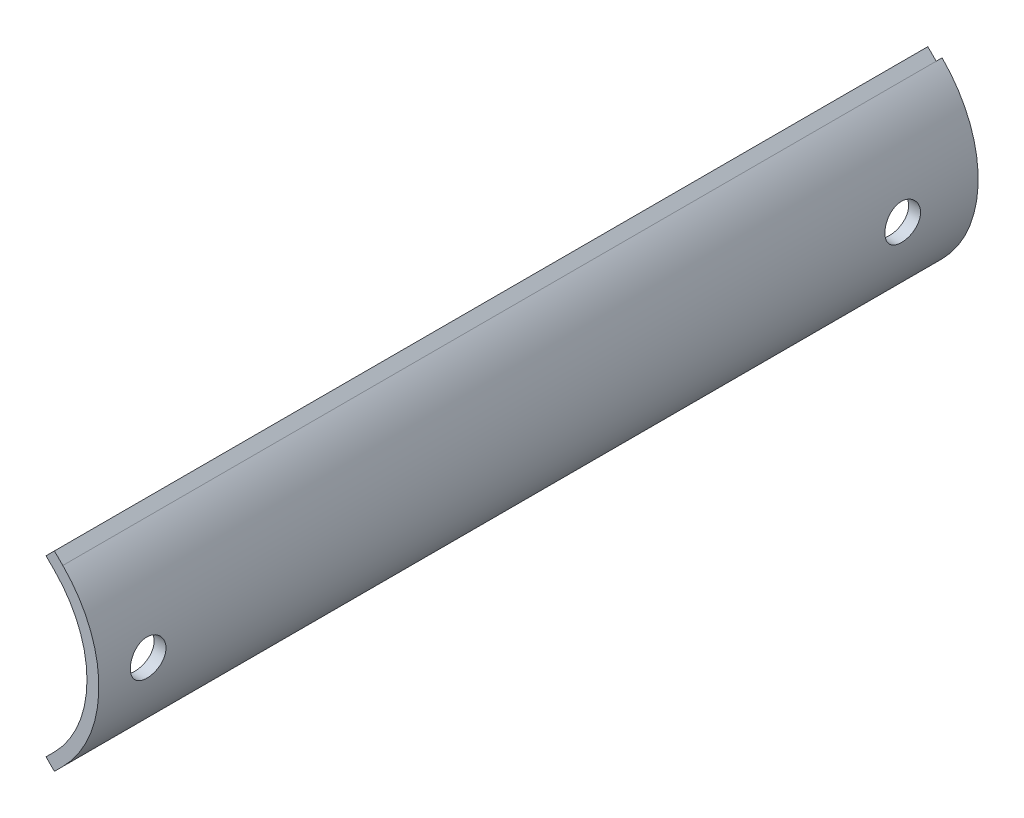
SolidWorks part; units mm, degrees
ref_plane "Front" through (0, 0, 0) normal (0, 0, 1) x (1, 0, 0)
ref_plane "Top" through (0, 0, 0) normal (0, 1, 0) x (1, 0, 0)
ref_plane "Right" through (0, 0, 0) normal (1, 0, 0) x (0, 0, -1)
sketch "Sketch1" plane through (0, 0, 0) normal (0, 0, 1) x (1, 0, 0)
  line L0 (6.6185, 6.6185) -> (7.3256, 7.3256)
  line L1 (6.6185, -6.6185) -> (7.3256, -7.3256)
  arc A0 (6.6185, 6.6185) -> (6.6185, -6.6185) centre (0, 0) cw
  arc A1 (7.3256, 7.3256) -> (7.3256, -7.3256) centre (0, 0) cw
extrude "Extrude1" add sketch "Sketch1" along normal blind 74
sketch "Sketch8" plane through (0, 0, 0) normal (1, 0, 0) x (0, 0, -1)
  line L0 (-74, 0) -> (0, 0) construction
  circle A0 centre (-6.35, 0) radius 1.5
  circle A2 centre (-69.85, 0) radius 1.5
extrude "Cut-Extrude4" cut sketch "Sketch8" along normal through all
sketch "Sketch9" plane through (0, 0, 0) normal (-0.7071, 0.7071, 0) x (0, 0, 1)
  line L1 (74, 10.36) -> (0, 10.36)
  line L2 (74, 10.36) -> (74, 9.36)
  line L3 (74, 9.36) -> (0, 9.36)
  line L4 (0, 10.36) -> (0, 9.36)
extrude "Extrude2" add sketch "Sketch9" along normal blind 1
sketch "Sketch10" plane through (0, 0, 0) normal (-0.7071, -0.7071, 0) x (0.7071, -0.7071, 0)
  line L1 (9.36, 74) -> (10.36, 74)
  line L2 (9.36, 74) -> (9.36, 0)
  line L3 (9.36, 0) -> (10.36, 0)
  line L4 (10.36, 74) -> (10.36, 0)
extrude "Extrude3" add sketch "Sketch10" along normal blind 1
sketch "Sketch12" plane through (-0.7071, 0.7071, 0) normal (-0.7071, 0.7071, 0) x (0, 0, 1)
  line L0 (0, 9.36) -> (74, 9.36) construction
  line L1 (0, 10.36) -> (0.4952, 10.36)
  line L2 (0, 10.36) -> (0, 9.36)
  line L3 (0, 9.36) -> (0.4952, 9.36)
  line L4 (0.4952, 10.36) -> (0.4952, 9.36)
extrude "Cut-Extrude5" cut sketch "Sketch12" against normal blind 1
sketch "Sketch13" plane through (6.6185, -6.6185, 0) normal (-0.7071, 0.7071, 0) x (-0.7071, -0.7071, 0)
  line L0 (1, 74) -> (1, 0) construction
  line L1 (0, 0) -> (1, 0)
  line L2 (0, 0) -> (0, 0.4982)
  line L3 (0, 0.4982) -> (1, 0.4982)
  line L4 (1, 0) -> (1, 0.4982)
extrude "Cut-Extrude6" cut sketch "Sketch13" against normal blind 1
